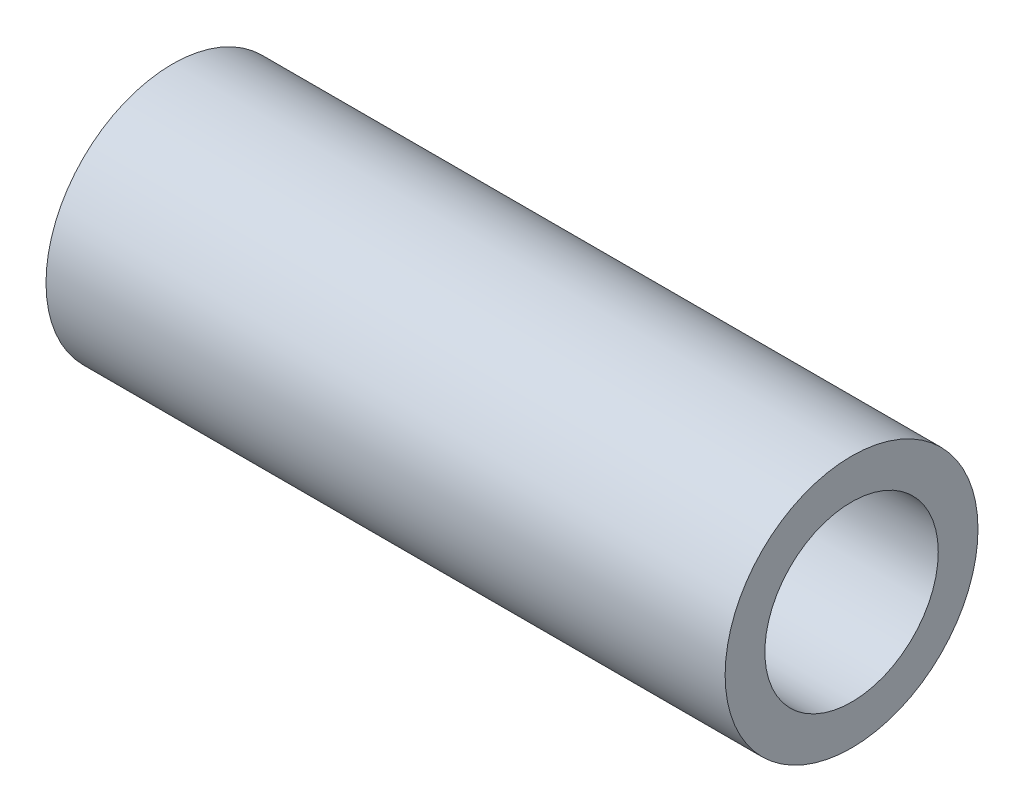
SolidWorks part; units mm, degrees
ref_plane "Front Plane" through (0, 0, 0) normal (0, 0, 1) x (1, 0, 0)
ref_plane "Top Plane" through (0, 0, 0) normal (0, 1, 0) x (1, 0, 0)
ref_plane "Right Plane" through (0, 0, 0) normal (1, 0, 0) x (0, 0, -1)
sketch "Sketch1" plane through (0, 0, 0) normal (1, 0, 0) x (0, 0, -1)
  circle A0 centre (0, 0) radius 3.048
  circle A1 centre (0, 0) radius 4.445
  dimension "D1" = 6.096
  dimension "D2" = 8.89
extrude "Boss-Extrude1" add sketch "Sketch1" along normal blind 23.876 contours A1 A0
ref_plane "Plane1" through (11.938, 0, 0) normal (-1, 0, 0) x (0, 0, 1)
